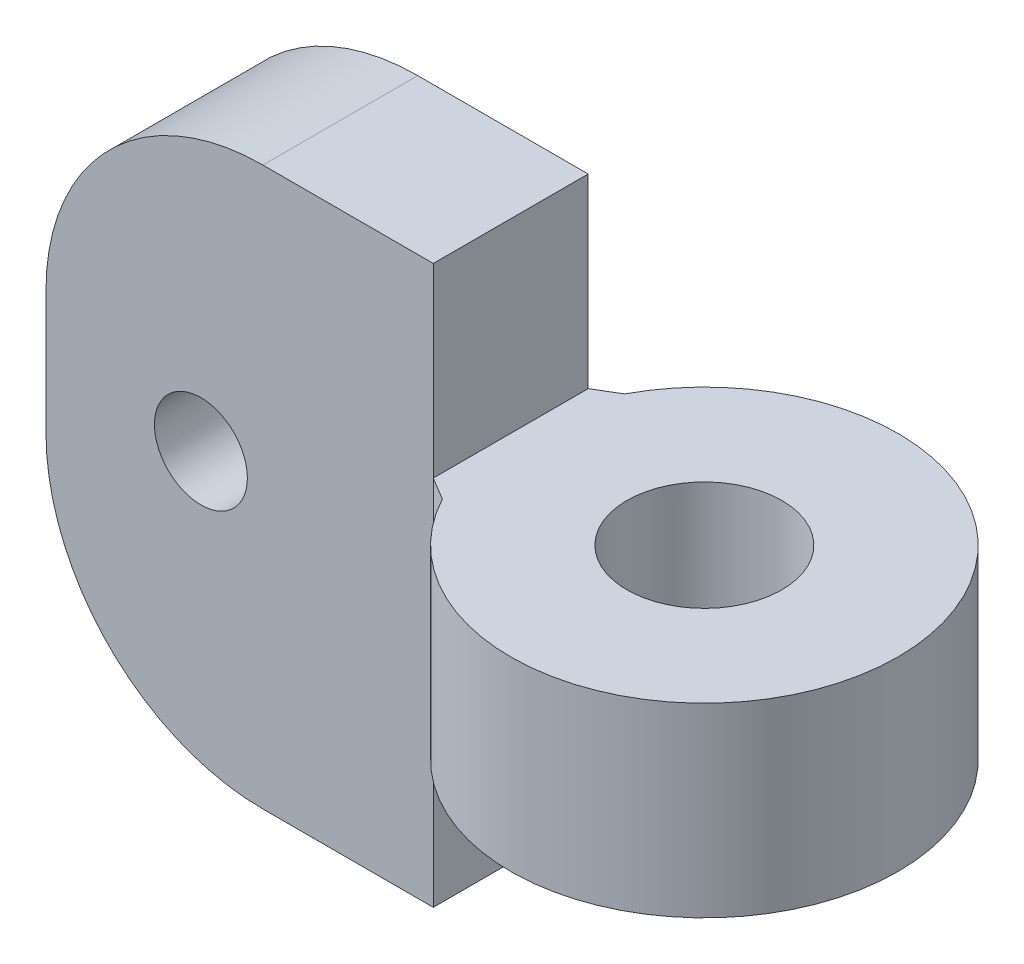
SolidWorks part; units mm, degrees
ref_plane "Alzado" through (0, 0, 0) normal (0, 0, 1) x (1, 0, 0)
ref_plane "Planta" through (0, 0, 0) normal (0, 1, 0) x (1, 0, 0)
ref_plane "Vista lateral" through (0, 0, 0) normal (1, 0, 0) x (0, 0, -1)
sketch "Croquis1" plane through (0, 0, 0) normal (0, 0, 1) x (1, 0, 0)
  line L0 (11.25, 17.1) -> (11.25, 11.1)
  line L1 (5.75, -0.9) -> (11.25, -0.9)
  line L2 (-1.25, 6.1) -> (-1.25, 10.1)
  line L3 (5.75, 17.1) -> (11.25, 17.1)
  line L4 (11.25, 11.1) -> (23.75, 11.1)
  line L5 (-1.25, -0.9) -> (1.25, 0.9) construction
  line L6 (-1.25, 17.1) -> (-1.0254, 14.0276) construction
  line L7 (23.75, 11.1) -> (23.75, 5.1)
  line L9 (23.75, 5.1) -> (11.25, 5.1)
  line L10 (11.25, 5.1) -> (11.25, -0.9)
  line L13 (11.25, 17.1) -> (-1.25, 17.1) construction
  circle A0 centre (3.75, 8.1) radius 1.5
  arc A1 (-1.25, 10.1) -> (5.75, 17.1) centre (5.75, 10.1) cw
  arc A2 (5.75, -0.9) -> (-1.25, 6.1) centre (5.75, 6.1) cw
  point P0 (0, 0)
  dimension "D6" = 3
  dimension "D4" = 7
  dimension "D5" = 7
  dimension "D1" = 25
  dimension "D2" = 18
  dimension "D3" = 12.5
  dimension "D7" = 5
  dimension "D8" = 9
  dimension "D9" = 6
  dimension "D10" = 6
extrude "Saliente-Extruir1" add sketch "Croquis1" along normal blind 15
sketch "Croquis2" plane through (0, 0, 0) normal (0, 1, 0) x (1, 0, 0)
  line L0 (23.75, -7.5) -> (11.25, -7.5) construction
  line L1 (23.75, -15) -> (23.75, 0) construction
  line L2 (11.25, -15) -> (11.25, 0) construction
  line L3 (17.5, -1.25) -> (11.25, 0)
  line L4 (17.5, -13.75) -> (11.25, -15)
  line L5 (11.25, -15) -> (11.25, -17.9613)
  line L6 (11.25, -17.9613) -> (29.6635, -17.9613)
  line L7 (29.6635, -17.9613) -> (29.6635, 1.8686)
  line L8 (29.6635, 1.8686) -> (11.1263, 1.8686)
  line L9 (11.1263, 1.8686) -> (11.25, 0)
  circle A0 centre (17.5, -7.5) radius 2.5
  arc A1 (17.5, -13.75) -> (17.5, -1.25) centre (17.5, -7.5) ccw
  dimension "D1" = 5
extrude "Cortar-Extruir1" cut sketch "Croquis2" along normal blind 20
sketch "Croquis3" plane through (0, 17.1, 0) normal (0, 1, 0) x (1, 0, 0)
  line L0 (-1.25, -7.5) -> (23.75, -7.5) construction
  line L1 (-1.25, -15) -> (-1.25, 0) construction
  line L2 (17.5, -1.25) -> (17.5, -13.75) construction
  line L3 (-4.1301, -10) -> (11.25, -10)
  line L4 (-13.75, -10) -> (-13.75, -5)
  line L5 (-3.4648, -5) -> (11.25, -5)
  line L7 (-1.25, -7.5) -> (11.25, -5) construction
  line L8 (-1.25, -7.5) -> (11.25, -10) construction
  line L9 (11.9853, -4.5588) -> (11.25, -5)
  line L10 (11.9853, -10.4412) -> (11.25, -10)
  line L11 (17.5, -1.25) -> (17.5, 1.6772)
  line L12 (17.5, 1.6772) -> (-3.4648, 1.6772)
  line L13 (-3.4648, 1.6772) -> (-3.4648, -5)
  line L14 (17.5, -13.75) -> (17.5, -15.5814)
  line L15 (17.5, -15.5814) -> (-4.1301, -15.5814)
  line L16 (-4.1301, -15.5814) -> (-4.1301, -10)
  arc A0 (17.5, -13.75) -> (17.5, -1.25) centre (17.5, -7.5) ccw construction
  arc A1 (17.5, -1.25) -> (11.9853, -4.5588) centre (17.5, -7.5) ccw
  arc A2 (11.9853, -10.4412) -> (17.5, -13.75) centre (17.5, -7.5) ccw
  line M1 (11.25, 0) -> (5.75, 0)
  line M2 (5.75, 0) -> (5.75, -15)
  line M3 (5.75, -15) -> (11.25, -15)
  line M4 (11.25, -15) -> (11.25, 0)
  dimension "D1" = 5
  dimension "D2" = 25
extrude "Cortar-Extruir2" cut sketch "Croquis3" against normal blind 22 contours L12 L13 L5 L9 L11 M2 M1 M4 | L16 L15 L14 L10 L3 M4 M3 M2 | L3 M2 M3 M4 | L5 M2 M4 M1
ref_plane "Plano1" through (0, 0, 7.5) normal (0, 0, 1) x (1, 0, 0)
